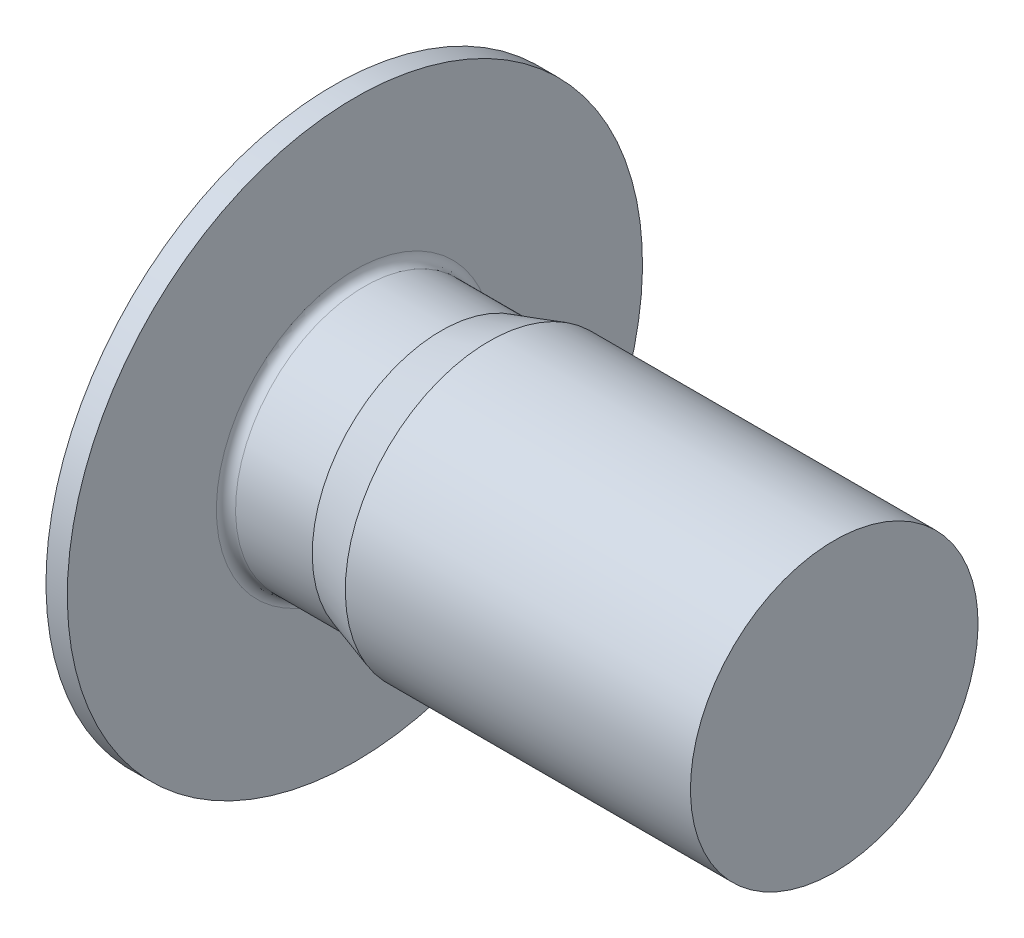
SolidWorks part; units mm, degrees
material "SCM435"
ref_plane "Front Plane" through (0, 0, 0) normal (0, 0, 1) x (1, 0, 0)
ref_plane "Top Plane" through (0, 0, 0) normal (0, 1, 0) x (1, 0, 0)
ref_plane "Right Plane" through (0, 0, 0) normal (1, 0, 0) x (0, 0, -1)
sketch "Sketch1" plane through (0, 0, 0) normal (0, 0, 1) x (1, 0, 0)
  line L0 (-0.8, 0) -> (5, 0) construction
  line L1 (-0.8, 0) -> (-0.8, 2)
  line L2 (-0.2226, 3) -> (0, 3)
  line L3 (0, 3) -> (0, 1.345)
  line L4 (1.4, 1.5) -> (5, 1.5)
  line L5 (5, 1.5) -> (5, 0)
  line L6 (5, 0) -> (-0.8, 0)
  line L7 (1.4, 1.5) -> (0.9, 1.345)
  line L8 (0.9, 1.345) -> (0, 1.345)
  line L9 (-0.2226, 3) -> (-0.8, 2)
  line L10 (-0.8, 0) -> (5, 0) construction
  dimension "A" = 6
  dimension "M" = 3
  dimension "L" = 5
  dimension "E" = 0.8
  dimension "FIX_1" = 30
  dimension "MSM_1" = 4
  dimension "MSM_2" = 2.69
  dimension "MSM_3" = 0.5
  dimension "E_s" = 1.4
revolve "Revolve1" add sketch "Sketch1" angle 360 about L0
cosmetic thread "Thread1" parameters "ATL_1"=3.6, "ATD"=2.459
fillet "Fillet1" radius 0.1 1 edges at (0, -1.345, 0)
sketch "Sketch2" plane through (-0.8, 0, 0) normal (-1, 0, 0) x (0, 0, 1)
  line L1 (0, 0.866) -> (-0.75, 0.433)
  line L2 (-0.75, 0.433) -> (-0.75, -0.433)
  line L3 (-0.75, -0.433) -> (0, -0.866)
  line L4 (0, -0.866) -> (0.75, -0.433)
  line L5 (0.75, -0.433) -> (0.75, 0.433)
  line L6 (0.75, 0.433) -> (0, 0.866)
  circle A0 centre (0, 0) radius 0.75 construction
  dimension "B" = 1.5
extrude "Cut-Extrude1" cut sketch "Sketch2" against normal blind 2
sketch "Sketch3" plane through (0, 0, 0) normal (0, 0, 1) x (1, 0, 0)
  line L0 (1.2, 0) -> (1.6506, 0) construction
  line L1 (1.2, 0) -> (1.2, 0.75)
  line L2 (1.2, 0.75) -> (1.6506, 0)
  line L3 (1.6506, 0) -> (1.2, 0)
  line L5 (1.2, 0.433) -> (1.2, -0.433) construction
  dimension "FIX_3" = 59
  dimension "B" = 1.5
revolve "Cut-Revolve1" cut sketch "Sketch3" angle 360 about L0
equation "\"ATL_1@Thread1\" = \"L@Sketch1\" - \"E_s@Sketch1\""
